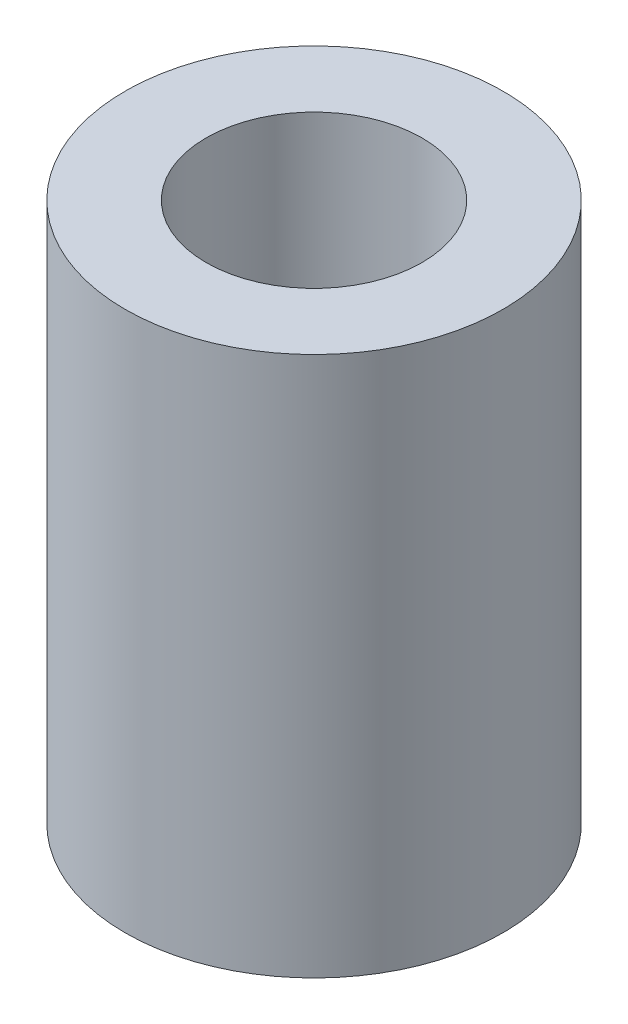
SolidWorks part; units mm, degrees
ref_plane "Front Plane" through (0, 0, 0) normal (0, 0, 1) x (1, 0, 0)
ref_plane "Top Plane" through (0, 0, 0) normal (0, 1, 0) x (1, 0, 0)
ref_plane "Right Plane" through (0, 0, 0) normal (1, 0, 0) x (0, 0, -1)
sketch "Sketch1" plane through (0, 0, 0) normal (0, 1, 0) x (1, 0, 0)
  circle A0 centre (0, 0) radius 6.35
  circle A1 centre (0, 0) radius 11.1125
  dimension "D1" = 12.7
  dimension "D2" = 22.225
extrude "Boss-Extrude1" add sketch "Sketch1" along normal blind 31.75
